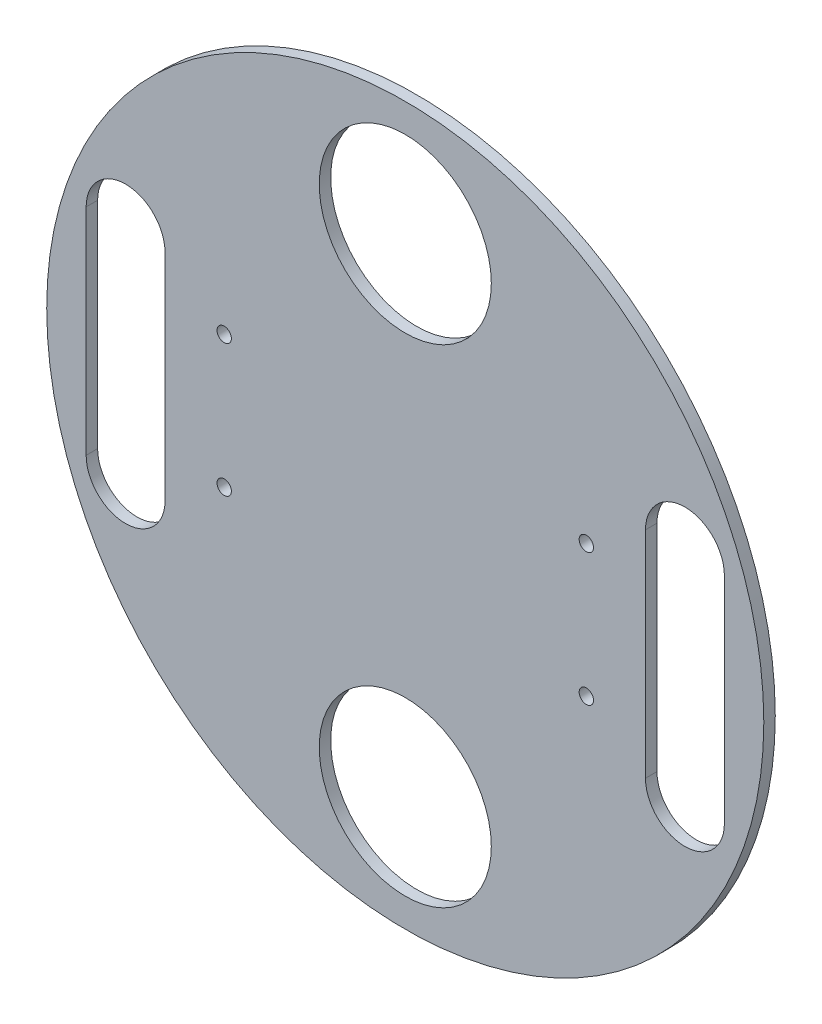
SolidWorks part; units mm, degrees
ref_plane "Plan de face" through (0, 0, 0) normal (0, 0, 1) x (1, 0, 0)
ref_plane "Plan de dessus" through (0, 0, 0) normal (0, 1, 0) x (1, 0, 0)
ref_plane "Plan de droite" through (0, 0, 0) normal (1, 0, 0) x (0, 0, -1)
sketch "Esquisse1" plane through (0, 0, 0) normal (0, 0, 1) x (1, 0, 0)
  circle A0 centre (0, 0) radius 50
  dimension "D1" = 100
extrude "Boss.-Extru.1" add sketch "Esquisse1" along normal blind 1.6
sketch "Esquisse2" plane through (0, 0, 1.6) normal (0, 0, 1) x (1, 0, 0)
  line L1 (-33.5, 15) -> (-33.5, -15)
  line L3 (-44.5, 15) -> (-44.5, -15)
  arc A0 (-44.5, 15) -> (-33.5, 15) centre (-39, 15) cw
  arc A2 (-44.5, -15) -> (-33.5, -15) centre (-39, -15) ccw
  dimension "D2" = 30
  dimension "D1" = 11
  dimension "D3" = 33.5
  dimension "D4" = 15
extrude "Enlèv. mat.-Extru.1" cut sketch "Esquisse2" against normal blind 1.6
mirror "Symétrie1" about plane through (0, 0, 0) normal (1, 0, 0) of "Enlèv. mat.-Extru.1"
sketch "Esquisse4" plane through (0, 0, 1.6) normal (0, 0, 1) x (1, 0, 0)
  circle A0 centre (0, 34) radius 12
  dimension "D1" = 24
  dimension "D2" = 34
extrude "Enlèv. mat.-Extru.3" cut sketch "Esquisse4" against normal blind 1.6
mirror "Symétrie6" about plane through (0, 0, 0) normal (0, 1, 0) of "Enlèv. mat.-Extru.3"
sketch "Esquisse7" plane through (0, 0, 1.6) normal (0, 0, 1) x (1, 0, 0)
  circle A0 centre (25.25, -9.2211) radius 1
extrude "Enlèv. mat.-Extru.4" cut sketch "Esquisse7" against normal blind 1.6
mirror "Symétrie7" about plane through (0, 0, 0) normal (0, 1, 0) of "Enlèv. mat.-Extru.4"
mirror "Symétrie8" about plane through (0, 0, 0) normal (1, 0, 0) of "Symétrie7", "Enlèv. mat.-Extru.4"
